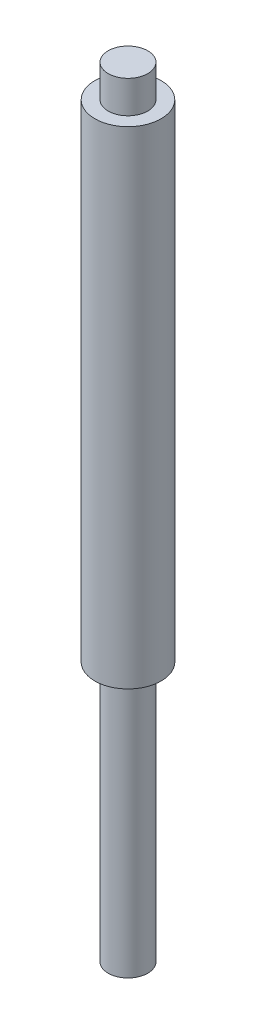
SolidWorks part; units mm, degrees
ref_plane "Front Plane" through (0, 0, 0) normal (0, 0, 1) x (1, 0, 0)
ref_plane "Top Plane" through (0, 0, 0) normal (0, 1, 0) x (1, 0, 0)
ref_plane "Right Plane" through (0, 0, 0) normal (1, 0, 0) x (0, 0, -1)
sketch "Sketch1" plane through (0, 0, 0) normal (0, 1, 0) x (1, 0, 0)
  circle A0 centre (0, 0) radius 0.61
  dimension "D1" = 1.22
sketch "Sketch2" plane through (0, 0, 0) normal (0, 1, 0) x (1, 0, 0)
  circle A0 centre (0, 0) radius 1.02
  circle A1 centre (0, 0) radius 0.61 construction
  dimension "D1" = 0.41
sketch "Sketch3" plane through (0, 0, 0) normal (1, 0, 0) x (0, 0, -1)
  line L0 (0.61, 0) -> (-0.61, 0) construction
  line L1 (-0.61, 0) -> (-1.02, 0) construction
  line L2 (0.61, 0) -> (1.02, 0) construction
  line L3 (0, 0) -> (0, 15) construction
  line L4 (0, 0) -> (0, -8) construction
  line L11 (1.02, 15) -> (-1.02, 15)
  line L12 (-1.02, 15) -> (-1.02, 0)
  line L13 (-1.02, 0) -> (-0.61, 0)
  line L14 (-0.61, 0) -> (-0.61, -8)
  line L15 (-0.61, -8) -> (0.61, -8)
  line L16 (0.61, -8) -> (0.61, 0)
  line L17 (0.61, 0) -> (1.02, 0)
  line L18 (1.02, 0) -> (1.02, 15)
  dimension "D1" = 8
  dimension "D2" = 15
extrude "Boss-Extrude1" add sketch "Sketch1" against normal up to vertex (8 mm away) up to point (0, -8, -0.61)
extrude "Boss-Extrude2" add sketch "Sketch2" along normal up to vertex (15 mm away) up to point (0, 15, -1.02)
sketch "Sketch4" plane through (0, 15, 0) normal (0, 1, 0) x (1, 0, 0)
  circle A0 centre (0, 0) radius 0.61 construction
  circle A1 centre (0, 0) radius 0.61
extrude "Boss-Extrude3" add sketch "Sketch4" along normal blind 1
